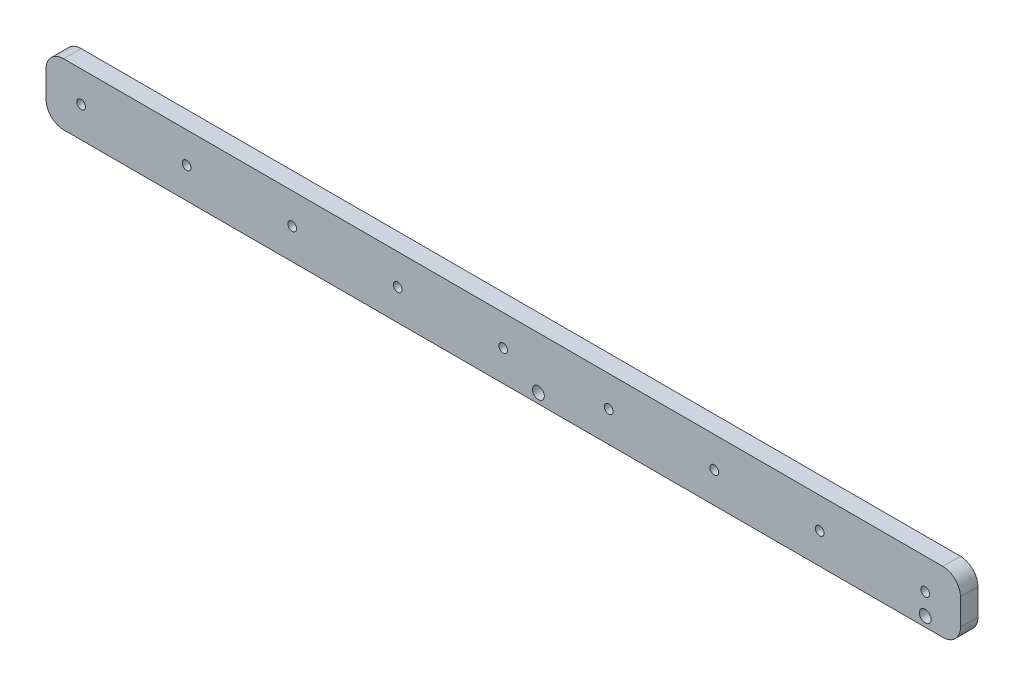
SolidWorks part; units mm, degrees
ref_plane "Plan de face" through (0, 0, 0) normal (0, 0, 1) x (1, 0, 0)
ref_plane "Plan de dessus" through (0, 0, 0) normal (0, 1, 0) x (1, 0, 0)
ref_plane "Plan de droite" through (0, 0, 0) normal (1, 0, 0) x (0, 0, -1)
sketch "Esquisse1" plane through (0, 0, 0) normal (0, 0, 1) x (1, 0, 0)
  line L0 (-280, 0) -> (-240, 0) construction
  line L1 (-250, 17.5) -> (250, 17.5)
  line L2 (-260, 7.5) -> (-260, -7.5)
  line L3 (-250, -17.5) -> (250, -17.5)
  line L4 (260, 7.5) -> (260, -7.5)
  line L5 (-260, 17.5) -> (260, -17.5) construction
  line L6 (-260, -17.5) -> (260, 17.5) construction
  circle A0 centre (-240, 0) radius 7
  circle A1 centre (-180, 0) radius 7
  circle A2 centre (-120, 0) radius 7
  circle A3 centre (-60, 0) radius 7
  circle A4 centre (0, 0) radius 7
  circle A5 centre (60, 0) radius 7
  circle A6 centre (120, 0) radius 7
  circle A7 centre (180, 0) radius 7
  circle A8 centre (240, 0) radius 7
  arc A9 (250, -17.5) -> (260, -7.5) centre (250, -7.5) ccw
  arc A10 (250, 17.5) -> (260, 7.5) centre (250, 7.5) cw
  arc A11 (-260, -7.5) -> (-250, -17.5) centre (-250, -7.5) ccw
  arc A12 (-250, 17.5) -> (-260, 7.5) centre (-250, 7.5) ccw
  point P0 (0, 0)
  point P11 (-260, 0)
  point P12 (-260, 0)
  dimension "D4" = 14
  dimension "D6" = 10
  dimension "D1" = 520
  dimension "D2" = 35
  dimension "D3" = 20
  dimension "D7" = 60
  dimension "D5" = 9
extrude "Boss.-Extru.1" add sketch "Esquisse1" along normal blind 10
sketch "Esquisse2" plane through (0, 0, 10) normal (0, 0, 1) x (1, 0, 0)
  circle A0 centre (-240, 0) radius 7 construction
  circle A1 centre (-240, 0) radius 7
  circle A2 centre (-180, 0) radius 7
  circle A3 centre (-120, 0) radius 7
  circle A4 centre (-60, 0) radius 7
  circle A5 centre (0, 0) radius 7
  circle A6 centre (60, 0) radius 7
  circle A7 centre (120, 0) radius 7
  circle A8 centre (180, 0) radius 7
  circle A9 centre (240, 0) radius 7
  circle A10 centre (-240, 0) radius 2.5
  circle A11 centre (-180, 0) radius 2.5
  circle A12 centre (-120, 0) radius 2.5
  circle A13 centre (-60, 0) radius 2.5
  circle A14 centre (0, 0) radius 2.5
  circle A15 centre (60, 0) radius 2.5
  circle A16 centre (120, 0) radius 2.5
  circle A17 centre (180, 0) radius 2.5
  circle A18 centre (240, 0) radius 2.5
  point P21 (0, 0)
  dimension "D2" = 9
  dimension "D3" = 5
  dimension "D4" = 60
  dimension "D1" = 9
extrude "Boss.-Extru.2" add sketch "Esquisse2" against normal blind 4
sketch "Esquisse3" plane through (0, 0, 10) normal (0, 0, 1) x (1, 0, 0)
  circle A0 centre (20, -12) radius 3.375
extrude "Enlèv. mat.-Extru.1" cut sketch "Esquisse3" against normal through all
sketch "Esquisse4" plane through (0, 0, 10) normal (0, 0, 1) x (1, 0, 0)
  circle A0 centre (240, -12) radius 3.375
extrude "Enlèv. mat.-Extru.2" cut sketch "Esquisse4" against normal through all
